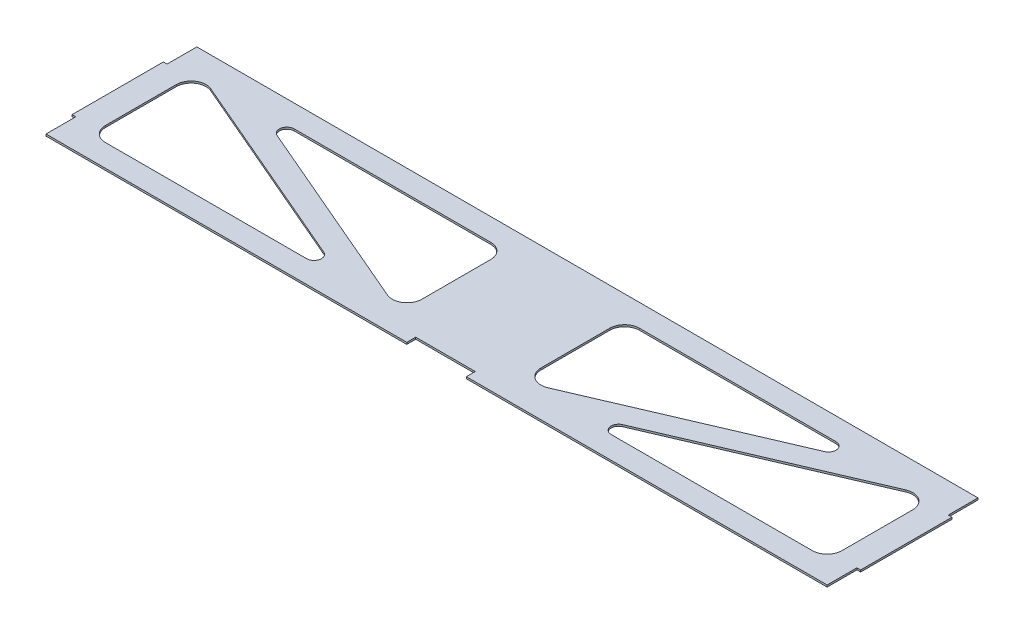
SolidWorks part; units mm, degrees
material "Balsa"
ref_plane "Front Plane" through (0, 0, 0) normal (0, 0, 1) x (1, 0, 0)
ref_plane "Top Plane" through (0, 0, 0) normal (0, 1, 0) x (1, 0, 0)
ref_plane "Right Plane" through (0, 0, 0) normal (1, 0, 0) x (0, 0, -1)
sketch "Sketch1" plane through (0, 0, 0) normal (0, 1, 0) x (1, 0, 0)
  line L0 (-333.375, 38.989) -> (-333.375, 64.389)
  line L1 (-333.375, -64.389) -> (333.375, -64.389)
  line L2 (-333.375, -64.389) -> (-333.375, -38.989)
  line L3 (-333.375, 64.389) -> (333.375, 64.389)
  line L4 (333.375, -64.389) -> (333.375, -38.989)
  line L5 (-333.375, -64.389) -> (333.375, 64.389) construction
  line L6 (-333.375, 64.389) -> (333.375, -64.389) construction
  line L7 (-333.375, 38.989) -> (-336.55, 38.989)
  line L9 (-333.375, -38.989) -> (-336.55, -38.989)
  line L10 (-336.55, 38.989) -> (-336.55, -38.989)
  line L12 (0, -1000) -> (0, 49000) construction
  line L13 (333.375, -38.989) -> (336.55, -38.989)
  line L14 (336.55, 38.989) -> (336.55, -38.989)
  line L15 (333.375, 38.989) -> (336.55, 38.989)
  line L16 (333.375, 38.989) -> (333.375, 64.389)
  point P0 (0, 0)
  dimension "D1" = 128.778
  dimension "D2" = 666.75
  dimension "D3" = 3.175
  dimension "D4" = 25.4
  dimension "D5" = 25.4
extrude "Boss-Extrude1" add sketch "Sketch1" along normal blind 1.5875
sketch "Sketch3" plane through (0, 1.5875, 0) normal (0, 1, 0) x (1, 0, 0)
  line L0 (-1000, 0) -> (49000, 0) construction
  line L1 (0, -1000) -> (0, 49000) construction
  line L2 (-314.325, 27.7608) -> (-314.325, -32.639)
  line L5 (-231.1832, 45.339) -> (-63.5, 45.339)
  line L6 (-50.8, 32.639) -> (-50.8, -26.0681)
  line L7 (-68.5088, -37.7386) -> (-233.6876, 33.1537)
  line L8 (-333.375, 64.389) -> (-333.375, 38.989) construction
  line L9 (-301.625, -45.339) -> (-129.9977, -45.339)
  line L10 (333.375, 64.389) -> (-333.375, 64.389) construction
  line L11 (68.5088, -37.7386) -> (233.6876, 33.1537)
  line L12 (50.8, 32.639) -> (50.8, -26.0681)
  line L13 (231.1832, 45.339) -> (63.5, 45.339)
  line L16 (314.325, 27.7608) -> (314.325, -32.639)
  line L19 (301.625, -45.339) -> (129.9977, -45.339)
  line L23 (-296.6162, 39.4313) -> (-127.4933, -33.1537)
  line L25 (296.6162, 39.4313) -> (127.4933, -33.1537)
  line L26 (-333.375, -64.389) -> (333.375, -64.389) construction
  arc A0 (-50.8, -26.0681) -> (-68.5088, -37.7386) centre (-63.5, -26.0681) cw
  arc A1 (-63.5, 45.339) -> (-50.8, 32.639) centre (-63.5, 32.639) cw
  arc A2 (-314.325, -32.639) -> (-301.625, -45.339) centre (-301.625, -32.639) ccw
  arc A3 (-314.325, 27.7608) -> (-296.6162, 39.4313) centre (-301.625, 27.7608) cw
  arc A4 (-231.1832, 45.339) -> (-233.6876, 33.1537) centre (-231.1832, 38.989) ccw
  arc A7 (231.1832, 45.339) -> (233.6876, 33.1537) centre (231.1832, 38.989) cw
  arc A8 (314.325, 27.7608) -> (296.6162, 39.4313) centre (301.625, 27.7608) ccw
  arc A9 (314.325, -32.639) -> (301.625, -45.339) centre (301.625, -32.639) cw
  arc A10 (63.5, 45.339) -> (50.8, 32.639) centre (63.5, 32.639) ccw
  arc A11 (50.8, -26.0681) -> (68.5088, -37.7386) centre (63.5, -26.0681) ccw
  arc A16 (-127.4933, -33.1537) -> (-129.9977, -45.339) centre (-129.9977, -38.989) cw
  arc A17 (127.4933, -33.1537) -> (129.9977, -45.339) centre (129.9977, -38.989) ccw
  point P15 (-333.375, 51.689)
  point P22 (-50.8, -45.339)
  point P27 (-323.85, -45.339)
  point P30 (-323.85, 45.339)
  point P33 (-262.0793, 45.339)
  point P54 (262.0793, 45.339)
  point P55 (323.85, 45.339)
  point P56 (323.85, -45.339)
  point P57 (50.8, -45.339)
  dimension "D6" = 12.7
  dimension "D7" = 6.35
  dimension "D8" = 19.05
  dimension "D9" = 19.05
  dimension "D2" = 6.35
  dimension "D5" = 6.35
  dimension "D1" = 19.05
  dimension "D3" = 19.05
  dimension "D4" = 50.8
extrude "Cut-Extrude2" cut sketch "Sketch3" against normal through all
sketch "Wing Spar Cut" plane through (0, 1.5875, 0) normal (0, 1, 0) x (1, 0, 0)
  line L0 (-333.375, -64.389) -> (333.375, -64.389) construction
  line L1 (25.4, -64.389) -> (-25.4, -64.389)
  line L2 (25.4, -64.389) -> (25.4, -56.769)
  line L3 (25.4, -56.769) -> (-25.4, -56.769)
  line L4 (-25.4, -64.389) -> (-25.4, -56.769)
  line L5 (333.375, 64.389) -> (-333.375, 64.389) construction
  point P6 (0, -56.769)
  point P9 (0, 64.389)
  dimension "D1" = 50.8
  dimension "D2" = 7.62
extrude "Cut-Extrude3" cut sketch "Wing Spar Cut" against normal through all
